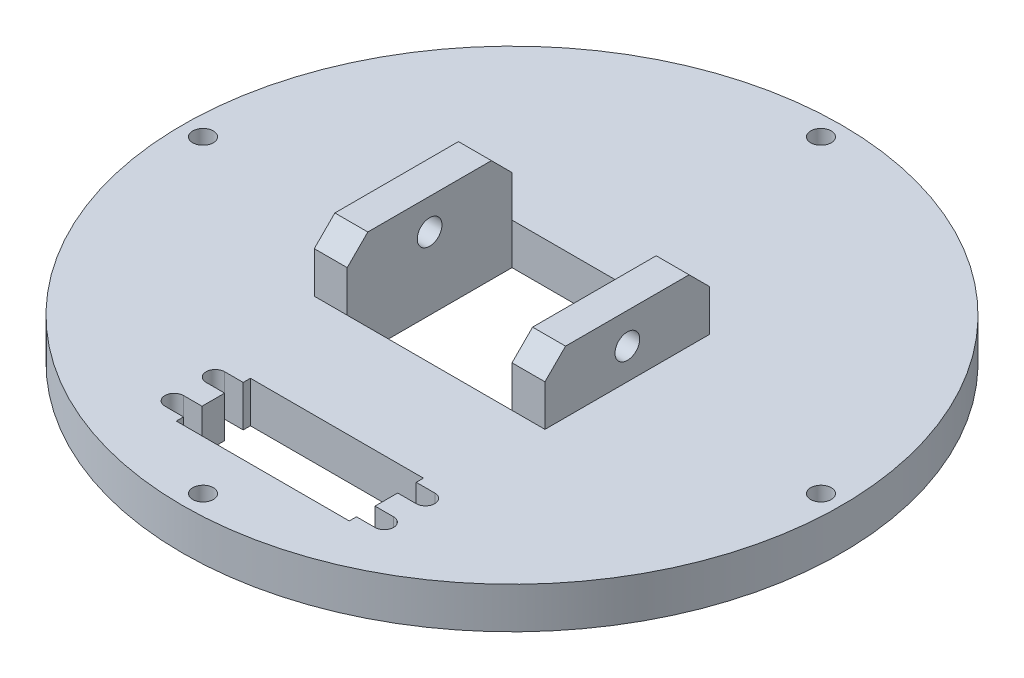
SolidWorks part; units mm, degrees
ref_plane "Front Plane" through (0, 0, 0) normal (0, 0, 1) x (1, 0, 0)
ref_plane "Top Plane" through (0, 0, 0) normal (0, 1, 0) x (1, 0, 0)
ref_plane "Right Plane" through (0, 0, 0) normal (1, 0, 0) x (0, 0, -1)
sketch "Sketch1" plane through (0, 0, 0) normal (0, 1, 0) x (1, 0, 0)
  circle A0 centre (0, 0) radius 80
  dimension "D1" = 160
extrude "Boss-Extrude1" add sketch "Sketch1" along normal blind 10 contours A0
sketch "Sketch2" plane through (0, 10, 0) normal (0, 1, 0) x (1, 0, 0)
  circle A0 centre (0, 0) radius 75 construction
  circle A1 centre (-75, 0) radius 2.5
  circle A2 centre (0, 75) radius 2.5
  circle A3 centre (75, 0) radius 2.5
  circle A4 centre (0, -75) radius 2.5
  point P3 (0, 75)
  point P4 (75, 0)
  point P5 (0, -75)
  point P6 (-75, 0)
  point P7 (-75, 0)
  dimension "D1" = 150
extrude "Cut-Extrude1" cut sketch "Sketch2" against normal up to next
sketch "Sketch3" plane through (0, 10, 0) normal (0, 1, 0) x (1, 0, 0)
  line L1 (-20, 20) -> (20, 20)
  line L2 (-20, 20) -> (-20, -20)
  line L3 (-20, -20) -> (20, -20)
  line L4 (20, 20) -> (20, -20)
  dimension "D1" = 40
  dimension "D2" = 20
  dimension "D3" = 20
extrude "Cut-Extrude2" cut sketch "Sketch3" against normal up to next
sketch "Sketch4" plane through (0, 10, 0) normal (0, 1, 0) x (1, 0, 0)
  line L0 (20, -20) -> (20, 20) construction
  line L1 (-18.5, -45) -> (23.5, -45)
  line L2 (-18.5, -45) -> (-18.5, -63)
  line L3 (-18.5, -63) -> (23.5, -63)
  line L4 (23.5, -45) -> (23.5, -63)
  line L5 (-20, -20) -> (20, -20) construction
  line L6 (-23, -59) -> (-18.5, -59) construction
  line L7 (-23, -49) -> (-23, -59)
  line L8 (-23, -49) -> (-18.5, -49) construction
  line L9 (-23, -46.75) -> (-18.5, -46.75)
  line L10 (-23, -51.25) -> (-18.5, -51.25)
  line L11 (28, -49) -> (28, -59)
  line L12 (-23, -56.75) -> (-18.5, -56.75)
  line L13 (-23, -61.25) -> (-18.5, -61.25)
  line L14 (23.5, -59) -> (28, -59) construction
  line L15 (23.5, -56.75) -> (28, -56.75)
  line L16 (23.5, -61.25) -> (28, -61.25)
  line L17 (23.5, -49) -> (28, -49) construction
  line L18 (23.5, -46.75) -> (28, -46.75)
  line L19 (23.5, -51.25) -> (28, -51.25)
  arc A2 (-23, -46.75) -> (-23, -51.25) centre (-23, -49) ccw
  arc A3 (-18.5, -51.25) -> (-18.5, -46.75) centre (-18.5, -49) ccw
  arc A4 (-23, -56.75) -> (-23, -61.25) centre (-23, -59) ccw
  arc A5 (-18.5, -61.25) -> (-18.5, -56.75) centre (-18.5, -59) ccw
  arc A6 (23.5, -56.75) -> (23.5, -61.25) centre (23.5, -59) ccw
  arc A7 (28, -61.25) -> (28, -56.75) centre (28, -59) ccw
  arc A8 (23.5, -46.75) -> (23.5, -51.25) centre (23.5, -49) ccw
  arc A9 (28, -51.25) -> (28, -46.75) centre (28, -49) ccw
  point P9 (-20.75, -59)
  point P12 (-20.75, -49)
  point P24 (25.75, -59)
  point P30 (25.75, -49)
  dimension "D5" = 4.5
  dimension "D8" = 4.5
  dimension "D10" = 2.25
  dimension "D9" = 2.25
  dimension "D11" = 2.25
  dimension "D12" = 2.25
  dimension "D1" = 42
  dimension "D2" = 18
  dimension "D3" = 3.5
  dimension "D4" = 25
  dimension "D6" = 10
  dimension "D7" = 4
extrude "Cut-Extrude3" cut sketch "Sketch4" against normal up to next
sketch "Sketch5" plane through (0, 10, 0) normal (0, 1, 0) x (1, 0, 0)
  line L0 (-20, -20) -> (20, -20) construction
  line L1 (-20, 20) -> (-28, 20)
  line L2 (-20, 20) -> (-20, -20)
  line L3 (-20, -20) -> (-28, -20)
  line L4 (-28, 20) -> (-28, -20)
  dimension "D1" = 8
extrude "Boss-Extrude2" add sketch "Sketch5" along normal blind 15
fillet "Fillet1" radius 5 2 edges at (-24, 25, -20) (-24, 25, 20) profile chamfer
sketch "Sketch6" plane through (-28, 0, 0) normal (-1, 0, 0) x (0, 0, 1)
  line L0 (-15, 25) -> (15, 25) construction
  line L2 (20, 20) -> (20, 10) construction
  circle A0 centre (0, 17.5) radius 3
  dimension "D1" = 6
  dimension "D2" = 7.5
  dimension "D3" = 20
extrude "Cut-Extrude4" cut sketch "Sketch6" against normal up to next
ref_plane "Plane1" [suppressed] through (0, 0, 0) normal (-1, 0, 0) x (0, 0, 1)
mirror "Mirror1" about plane through (0, 0, 0) normal (-1, 0, 0) of "Cut-Extrude4", "Fillet1", "Boss-Extrude2"
